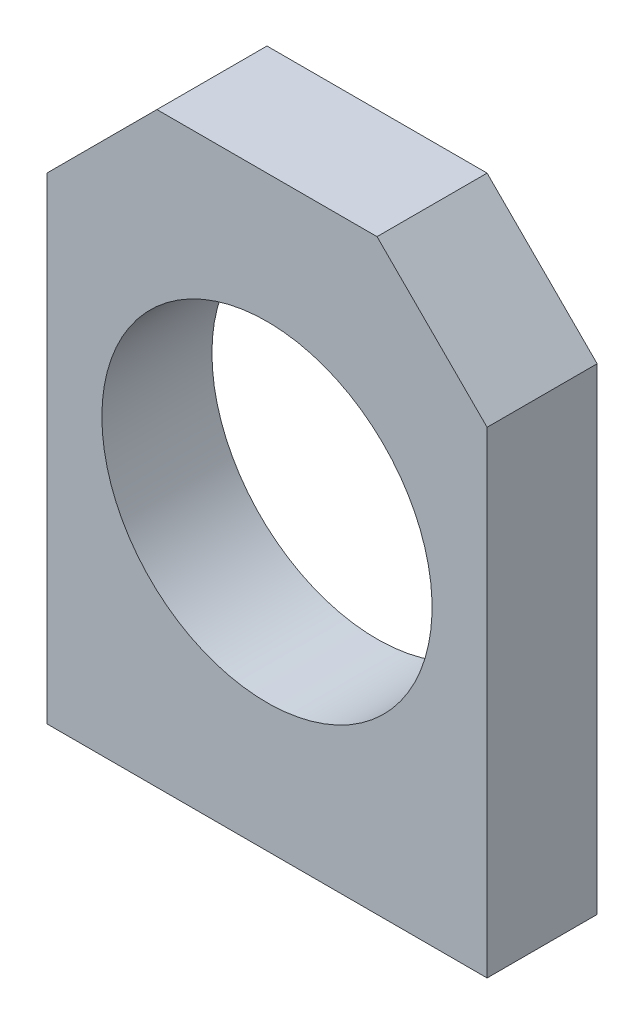
SolidWorks part; units mm, degrees
material "Plain Carbon Steel"
ref_plane "Front Plane" through (0, 0, 0) normal (0, 0, 1) x (1, 0, 0)
ref_plane "Top Plane" through (0, 0, 0) normal (0, 1, 0) x (1, 0, 0)
ref_plane "Right Plane" through (0, 0, 0) normal (1, 0, 0) x (0, 0, -1)
sketch "Sketch1" plane through (0, 0, 0) normal (0, 1, 0) x (1, 0, 0)
  line L0 (19.05, 0) -> (-19.05, 0)
  line L1 (-19.05, 0) -> (-19.05, -9.525)
  line L2 (-19.05, -9.525) -> (19.05, -9.525)
  line L3 (19.05, -9.525) -> (19.05, 0)
  line L4 (0, 0) -> (0, -58.7554) construction
  point P4 (0, 0)
  dimension "D2" = 9.525
  dimension "D3" = 38.1
extrude "Boss-Extrude1" add sketch "Sketch1" along normal mid plane 50.8
sketch "Sketch3" plane through (0, 0, 0) normal (0, 0, -1) x (-1, 0, 0)
  circle A0 centre (0, 0) radius 14.2875
  dimension "D1" = 28.575
extrude "Cut-Extrude1" cut sketch "Sketch3" against normal through all
sketch "Sketch4" plane through (0, 0, 0) normal (0, 0, -1) x (-1, 0, 0)
  line L0 (-9.525, 25.4) -> (-19.05, 15.875)
  line L1 (-19.05, 25.4) -> (19.05, 25.4) construction
  line L2 (-19.05, 15.875) -> (-19.05, 25.4)
  line L3 (-19.05, 25.4) -> (-9.525, 25.4)
  line L4 (-19.05, 25.4) -> (-19.05, -25.4) construction
  line L5 (9.525, 25.4) -> (19.05, 25.4)
  line L6 (19.05, 25.4) -> (19.05, 15.875)
  line L7 (19.05, 25.4) -> (19.05, -25.4) construction
  line L8 (19.05, 15.875) -> (9.525, 25.4)
  dimension "D1" = 45
  dimension "D2" = 9.525
extrude "Cut-Extrude2" cut sketch "Sketch4" against normal through all
